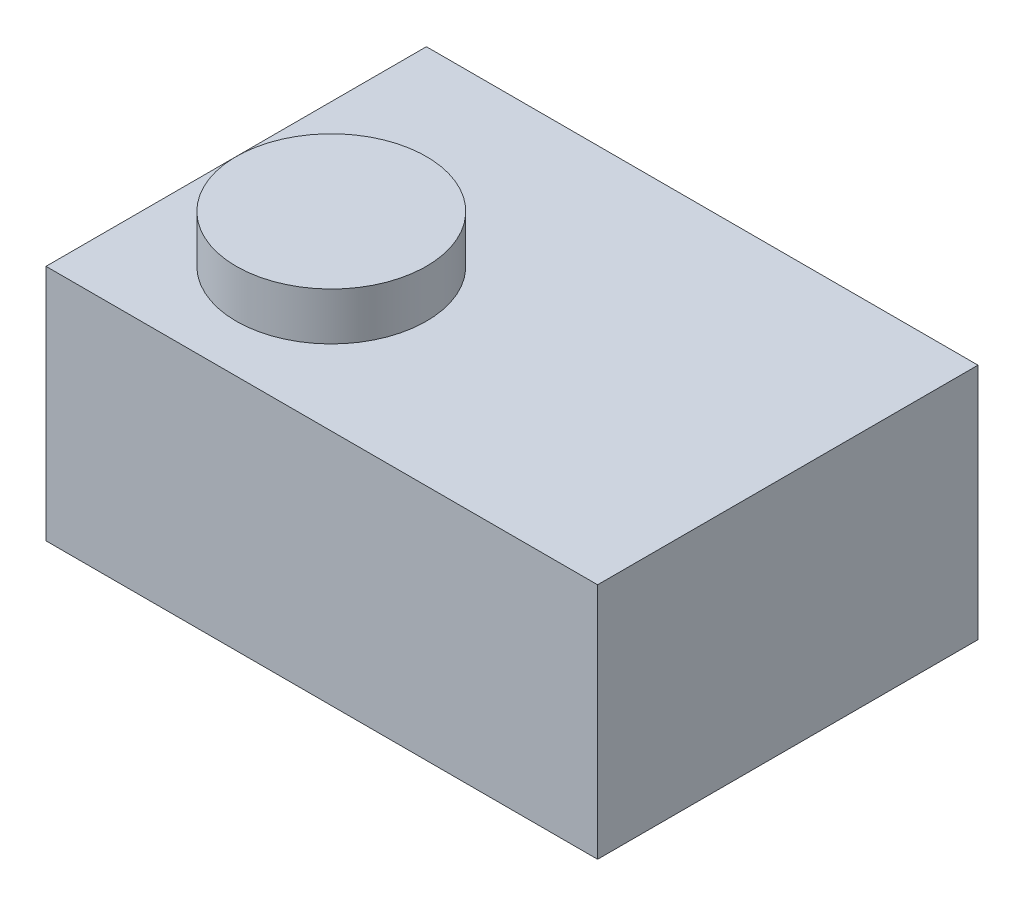
SolidWorks part; units mm, degrees
material "ABS"
ref_plane "Front Plane" through (0, 0, 0) normal (0, 0, 1) x (1, 0, 0)
ref_plane "Top Plane" through (0, 0, 0) normal (0, 1, 0) x (1, 0, 0)
ref_plane "Right Plane" through (0, 0, 0) normal (1, 0, 0) x (0, 0, -1)
sketch "Sketch1" plane through (0, 0, 0) normal (0, 1, 0) x (1, 0, 0)
  line L1 (-27.8266, 20.578) -> (30.1734, 20.578)
  line L2 (-27.8266, 20.578) -> (-27.8266, -19.422)
  line L3 (-27.8266, -19.422) -> (30.1734, -19.422)
  line L4 (30.1734, 20.578) -> (30.1734, -19.422)
  dimension "D1" = 40
  dimension "D2" = 58
extrude "Boss-Extrude1" add sketch "Sketch1" along normal blind 25
sketch "Sketch2" plane through (0, 25, 0) normal (0, 1, 0) x (1, 0, 0)
  line L0 (-27.8266, 20.578) -> (-27.8266, -19.422) construction
  line L2 (-27.8266, -19.422) -> (30.1734, -19.422) construction
  circle A0 centre (-12.8266, -4.422) radius 10
  dimension "D1" = 20
  dimension "D2" = 15
  dimension "D4" = 15
extrude "Boss-Extrude2" add sketch "Sketch2" along normal blind 5
